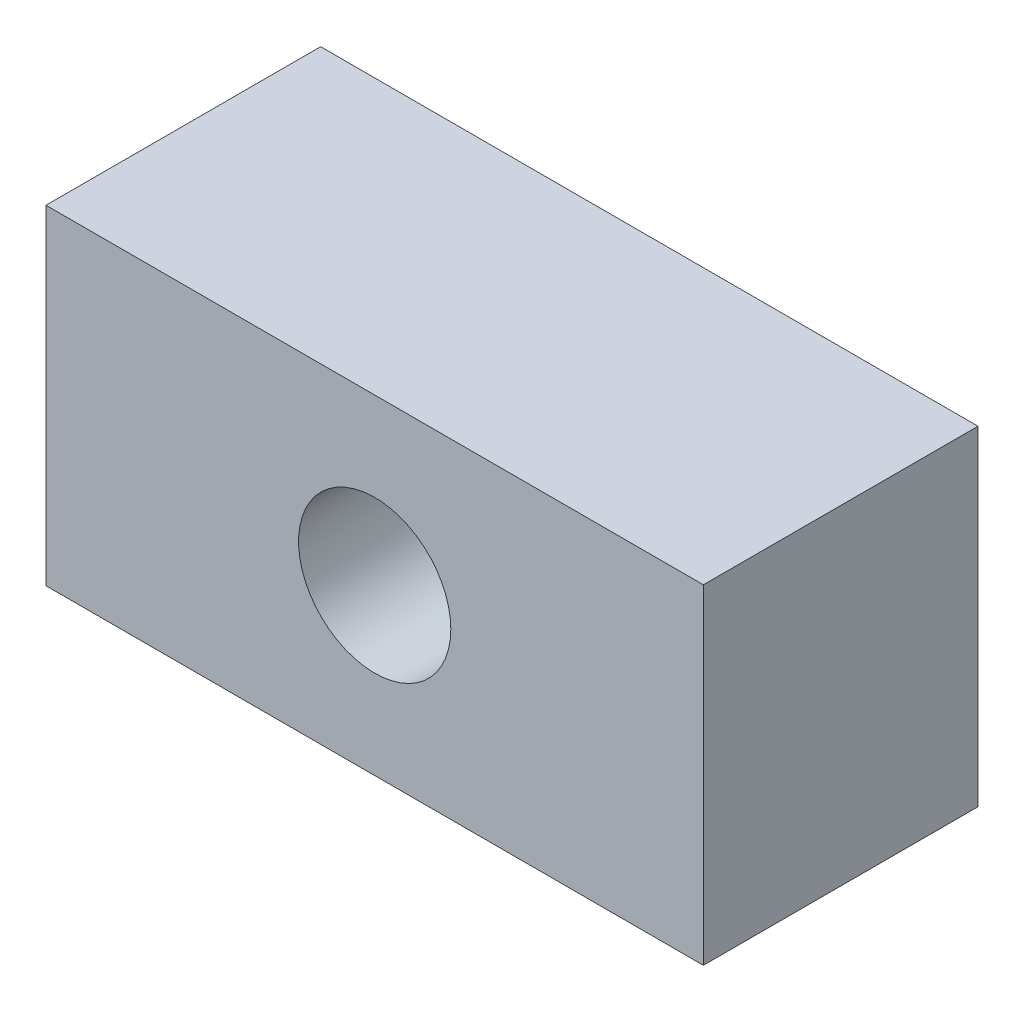
SolidWorks part; units mm, degrees
material "Low Carbon Steel"
ref_plane "Front Plane" through (0, 0, 0) normal (0, 0, 1) x (1, 0, 0)
ref_plane "Top Plane" through (0, 0, 0) normal (0, 1, 0) x (1, 0, 0)
ref_plane "Right Plane" through (0, 0, 0) normal (1, 0, 0) x (0, 0, -1)
sketch "Sketch1" plane through (0, 0, 0) normal (1, 0, 0) x (0, 0, -1)
  line L0 (-7.9375, 9.525) -> (7.9375, -9.525) construction
  line L1 (-7.9375, 9.525) -> (7.9375, 9.525)
  line L2 (-7.9375, 9.525) -> (-7.9375, -9.525)
  line L3 (-7.9375, -9.525) -> (7.9375, -9.525)
  line L4 (7.9375, 9.525) -> (7.9375, -9.525)
  line L5 (7.9375, -9.525) -> (7.82, -9.655) construction
  dimension "D1" = 15.875
  dimension "D2" = 19.05
extrude "Boss-Extrude1" add sketch "Sketch1" along normal mid plane 38
hole_wizard "M10x1.25 Tapped Hole1" positions "Sketch3" profile "Sketch2" tap size "M10x1.25" standard "ANSI Metric" end condition through all
sketch "Sketch3" plane through (0, 0, 7.9375) normal (0, 0, 1) x (1, 0, 0)
  point P0 (0, 0)
cosmetic thread "Hole Thread1" parameters "D2"=10
sketch "Sketch2" plane through (0, 0, 7.9375) normal (1, 0, 0) x (0, -1, 0)
  line L0 (0, 0) -> (0, 15.875)
  line L1 (0, 15.875) -> (4.4, 15.875)
  line L2 (4.4, 15.875) -> (4.4, 0)
  line L5 (4.4, 0) -> (0, 0)
  line L11 (0, -6.35) -> (0, 107.95) construction
  dimension "Thru Tap Drill Dia." = 8.8
  dimension "Thru Tap Drill Depth" = 15.875
other "Freeze***"
